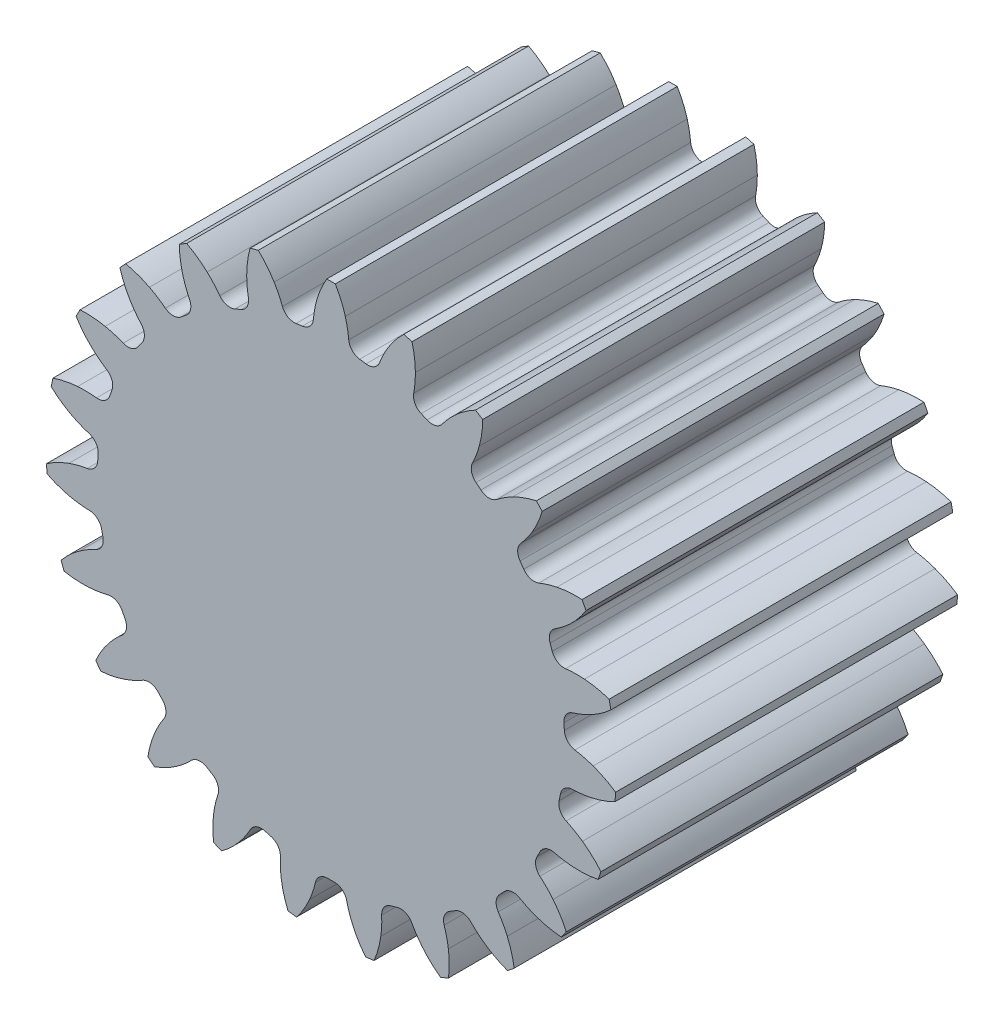
SolidWorks part; units mm, degrees
ref_plane "Front Plane" through (0, 0, 0) normal (0, 0, 1) x (1, 0, 0)
ref_plane "Top Plane" through (0, 0, 0) normal (0, 1, 0) x (1, 0, 0)
ref_plane "Right Plane" through (0, 0, 0) normal (1, 0, 0) x (0, 0, -1)
sketch "Sketch1" plane through (0, 0, 0) normal (0, 0, 1) x (1, 0, 0)
  line L0 (0, 50) -> (0, -50) construction
  circle A0 centre (0, 0) radius 46 construction
  circle A1 centre (0, 0) radius 50 construction
  arc A2 (-5.0261, 40.6908) -> (-6.1385, 40.5379) centre (0, 0) ccw
  arc A3 (-0.75, 49.9944) -> (0.75, 49.9944) centre (0, 0) cw
  arc A4 (0.75, 49.9944) -> (2.5, 45.932) centre (-13.7626, 41.3345) cw
  arc A5 (2.5, 45.932) -> (3.1051, 42.6729) centre (-14.8692, 41.0216) cw
  arc A6 (3.1051, 42.6729) -> (5.0261, 40.6908) centre (5.2958, 42.8742) ccw
  arc A7 (-3.1051, 42.6729) -> (-5.0261, 40.6908) centre (-5.2958, 42.8742) cw
  arc A8 (-2.5, 45.932) -> (-3.1051, 42.6729) centre (14.8692, 41.0216) ccw
  arc A9 (-0.75, 49.9944) -> (-2.5, 45.932) centre (13.7626, 41.3345) ccw
  arc A10 (8.5231, 41.9282) -> (6.1385, 40.5379) centre (6.4679, 42.7131) cw
  arc A11 (9.985, 44.9032) -> (8.5231, 41.9282) centre (25.3853, 35.4887) ccw
  arc A12 (12.7661, 48.3428) -> (9.985, 44.9032) centre (24.4042, 36.0886) ccw
  arc A13 (12.7661, 48.3428) -> (14.2105, 47.9381) centre (0, 0) cw
  arc A14 (14.2105, 47.9381) -> (14.7996, 43.5542) centre (-2.1004, 43.5148) cw
  arc A15 (14.7996, 43.5542) -> (14.5029, 40.2527) centre (-3.2503, 43.5121) cw
  arc A16 (14.5029, 40.2527) -> (15.818, 37.8258) centre (16.6668, 39.8555) ccw
  arc A17 (19.5191, 38.0739) -> (16.8478, 37.3785) centre (17.7519, 39.3842) cw
  arc A18 (21.7295, 40.5442) -> (19.5191, 38.0739) centre (34.0187, 27.3238) ccw
  arc A19 (25.3355, 43.1059) -> (21.7295, 40.5442) centre (33.2358, 28.1661) ccw
  arc A20 (25.3355, 43.1059) -> (26.6171, 42.3265) centre (0, 0) cw
  arc A21 (26.6171, 42.3265) -> (26.0016, 37.9462) centre (9.7177, 42.4678) cw
  arc A22 (26.0016, 37.9462) -> (24.8252, 34.8472) centre (8.6096, 42.7755) cw
  arc A23 (24.8252, 34.8472) -> (25.4367, 32.1555) centre (26.8016, 33.8809) ccw
  arc A24 (29.0675, 31.3958) -> (26.3077, 31.4469) centre (27.7193, 33.1343) cw
  arc A25 (31.8624, 33.1781) -> (29.0675, 31.3958) centre (40.1291, 17.1325) ccw
  arc A26 (36.0258, 34.6719) -> (31.8624, 33.1781) centre (39.6024, 18.1548) ccw
  arc A27 (36.0258, 34.6719) -> (37.0496, 33.5757) centre (0, 0) cw
  arc A28 (37.0496, 33.5757) -> (35.2752, 29.524) centre (20.815, 38.2712) cw
  arc A29 (35.2752, 29.524) -> (33.3063, 26.8572) centre (19.831, 38.8664) cw
  arc A30 (33.3063, 26.8572) -> (33.1689, 24.1003) centre (34.9487, 25.3935) ccw
  arc A31 (36.4601, 22.3893) -> (33.8164, 23.183) centre (35.6309, 24.427) cw
  arc A32 (39.6322, 23.3514) -> (36.4601, 22.3893) centre (43.2633, 5.6704) ccw
  arc A33 (44.0442, 23.6666) -> (39.6322, 23.3514) centre (43.0319, 6.7969) ccw
  arc A34 (44.0442, 23.6666) -> (44.7343, 22.3347) centre (0, 0) cw
  arc A35 (44.7343, 22.3347) -> (41.9325, 18.912) centre (30.3686, 31.2362) cw
  arc A36 (41.9325, 18.912) -> (39.3172, 16.8754) centre (29.5817, 32.0748) cw
  arc A37 (39.3172, 16.8754) -> (38.4411, 14.2578) centre (40.5038, 15.0228) ccw
  arc A38 (41.1486, 11.7222) -> (38.8171, 13.1998) centre (40.8999, 13.9081) cw
  arc A39 (44.4627, 11.7929) -> (41.1486, 11.7222) centre (43.1888, -6.2121) ccw
  arc A40 (48.7961, 10.906) -> (44.4627, 11.7929) centre (43.27, -5.065) ccw
  arc A41 (48.7961, 10.906) -> (49.1013, 9.4373) centre (0, 0) cw
  arc A42 (49.1013, 9.4373) -> (45.4799, 6.8974) centre (37.6698, 21.8845) cw
  arc A43 (45.4799, 6.8974) -> (42.4121, 5.6419) centre (37.1384, 22.9043) cw
  arc A44 (42.4121, 5.6419) -> (40.8623, 3.3578) centre (43.0549, 3.5379) ccw
  arc A45 (42.7853, 0.1857) -> (40.9389, 2.2376) centre (43.1356, 2.3577) cw
  arc A46 (45.9955, -0.6403) -> (42.7853, 0.1857) centre (39.9113, -17.634) ccw
  arc A47 (49.929, -2.6635) -> (45.9955, -0.6403) centre (40.2989, -16.5513) ccw
  arc A48 (49.929, -2.6635) -> (49.8266, -4.16) centre (0, 0) cw
  arc A49 (49.8266, -4.16) -> (45.6543, -5.6287) centre (42.1773, 10.9098) cw
  arc A50 (45.6543, -5.6287) -> (42.3615, -6.0099) centre (41.9407, 12.0352) cw
  arc A51 (42.3615, -6.0099) -> (40.2529, -7.7913) centre (42.4128, -8.2093) ccw
  arc A52 (41.2488, -11.3645) -> (40.0245, -8.8906) centre (42.1721, -9.3676) cw
  arc A53 (44.1171, -13.026) -> (41.2488, -11.3645) centre (33.6737, -27.748) ccw
  arc A54 (47.3589, -16.0354) -> (44.1171, -13.026) centre (34.339, -26.81) ccw
  arc A55 (47.3589, -16.0354) -> (46.8566, -17.4488) centre (0, 0) cw
  arc A56 (46.8566, -17.4488) -> (42.4427, -17.7373) centre (43.5567, -0.8741) cw
  arc A57 (42.4427, -17.7373) -> (39.1692, -17.2161) centre (43.6325, 0.2734) cw
  arc A58 (39.1692, -17.2161) -> (36.6582, -18.3624) centre (38.6252, -19.3478) ccw
  arc A59 (36.6531, -22.0719) -> (36.1416, -19.3593) centre (38.0809, -20.3981) cw
  arc A60 (38.9668, -24.4457) -> (36.6531, -22.0719) centre (24.9386, -35.8041) ccw
  arc A61 (41.2764, -28.218) -> (38.9668, -24.4457) centre (25.8324, -35.0804) ccw
  arc A62 (41.2764, -28.218) -> (40.4114, -29.4435) centre (0, 0) cw
  arc A63 (40.4114, -29.4435) -> (36.0834, -28.5305) centre (41.7056, -12.5931) cw
  arc A64 (36.0834, -28.5305) -> (33.0718, -27.1454) centre (42.0882, -11.5086) cw
  arc A65 (33.0718, -27.1454) -> (30.3446, -27.5718) centre (31.9729, -29.0512) ccw
  arc A66 (29.339, -31.1423) -> (29.5783, -28.3923) centre (31.1654, -29.9158) cw
  arc A67 (30.9264, -34.0523) -> (29.339, -31.1423) centre (14.354, -41.2047) ccw
  arc A68 (32.1326, -38.3079) -> (30.9264, -34.0523) centre (15.4099, -40.749) ccw
  arc A69 (32.1326, -38.3079) -> (30.9691, -39.2545) centre (0, 0) cw
  arc A70 (30.9691, -39.2545) -> (27.0479, -37.2077) centre (36.7615, -23.3782) cw
  arc A71 (27.0479, -37.2077) -> (24.5217, -35.0614) centre (37.4225, -22.4371) cw
  arc A72 (24.5217, -35.0614) -> (21.7806, -34.7362) centre (22.9493, -36.6001) ccw
  arc A73 (19.8489, -37.903) -> (20.8213, -35.3196) centre (21.9385, -37.2148) cw
  arc A74 (20.5924, -41.1334) -> (19.8489, -37.903) centre (2.7048, -43.5494) ccw
  arc A75 (20.6057, -45.5566) -> (20.5924, -41.1334) centre (3.8445, -43.3955) ccw
  arc A76 (20.6057, -45.5566) -> (19.2299, -46.1542) centre (0, 0) cw
  arc A77 (19.2299, -46.1542) -> (16.0063, -43.1254) centre (29.0909, -32.4294) cw
  arc A78 (16.0063, -43.1254) -> (14.1529, -40.3771) centre (29.9813, -31.7016) cw
  arc A79 (14.1529, -40.3771) -> (11.6012, -39.3244) centre (12.2237, -41.4345) ccw
  arc A80 (8.8868, -41.8526) -> (10.5201, -39.6274) centre (11.0846, -41.7537) cw
  arc A81 (8.7311, -45.1638) -> (8.8868, -41.8526) centre (-9.145, -42.6642) ccw
  arc A82 (7.5506, -49.4266) -> (8.7311, -45.1638) centre (-8.006, -42.8235) ccw
  arc A83 (7.5506, -49.4266) -> (6.0646, -49.6308) centre (0, 0) cw
  arc A84 (6.0646, -49.6308) -> (3.7777, -45.8446) centre (19.2628, -39.0755) cw
  arc A85 (3.7777, -45.8446) -> (2.7345, -42.6982) centre (20.3165, -38.6148) cw
  arc A86 (2.7345, -42.6982) -> (0.5614, -40.9962) centre (0.5915, -43.196) ccw
  arc A87 (-2.7345, -42.6982) -> (-0.5614, -40.9962) centre (-0.5915, -43.196) cw
  arc A88 (-3.7777, -45.8446) -> (-2.7345, -42.6982) centre (-20.3165, -38.6148) ccw
  arc A89 (-6.0646, -49.6308) -> (-3.7777, -45.8446) centre (-19.2628, -39.0755) ccw
  arc A90 (-6.0646, -49.6308) -> (-7.5506, -49.4266) centre (0, 0) cw
  arc A91 (-7.5506, -49.4266) -> (-8.7311, -45.1638) centre (8.006, -42.8235) cw
  arc A92 (-8.7311, -45.1638) -> (-8.8868, -41.8526) centre (9.145, -42.6642) cw
  arc A93 (-8.8868, -41.8526) -> (-10.5201, -39.6274) centre (-11.0846, -41.7537) ccw
  arc A94 (-14.1529, -40.3771) -> (-11.6012, -39.3244) centre (-12.2237, -41.4345) cw
  arc A95 (-16.0063, -43.1254) -> (-14.1529, -40.3771) centre (-29.9813, -31.7016) ccw
  arc A96 (-19.2299, -46.1542) -> (-16.0063, -43.1254) centre (-29.0909, -32.4294) ccw
  arc A97 (-19.2299, -46.1542) -> (-20.6057, -45.5566) centre (0, 0) cw
  arc A98 (-20.6057, -45.5566) -> (-20.5924, -41.1334) centre (-3.8445, -43.3955) cw
  arc A99 (-20.5924, -41.1334) -> (-19.8489, -37.903) centre (-2.7048, -43.5494) cw
  arc A100 (-19.8489, -37.903) -> (-20.8213, -35.3196) centre (-21.9385, -37.2148) ccw
  arc A101 (-24.5217, -35.0614) -> (-21.7806, -34.7362) centre (-22.9493, -36.6001) cw
  arc A102 (-27.0479, -37.2077) -> (-24.5217, -35.0614) centre (-37.4225, -22.4371) ccw
  arc A103 (-30.9691, -39.2545) -> (-27.0479, -37.2077) centre (-36.7615, -23.3782) ccw
  arc A104 (-30.9691, -39.2545) -> (-32.1326, -38.3079) centre (0, 0) cw
  arc A105 (-32.1326, -38.3079) -> (-30.9264, -34.0523) centre (-15.4099, -40.749) cw
  arc A106 (-30.9264, -34.0523) -> (-29.339, -31.1423) centre (-14.354, -41.2047) cw
  arc A107 (-29.339, -31.1423) -> (-29.5783, -28.3923) centre (-31.1654, -29.9158) ccw
  arc A108 (-33.0718, -27.1454) -> (-30.3446, -27.5718) centre (-31.9729, -29.0512) cw
  arc A109 (-36.0834, -28.5305) -> (-33.0718, -27.1454) centre (-42.0882, -11.5086) ccw
  arc A110 (-40.4114, -29.4435) -> (-36.0834, -28.5305) centre (-41.7056, -12.5931) ccw
  arc A111 (-40.4114, -29.4435) -> (-41.2764, -28.218) centre (0, 0) cw
  arc A112 (-41.2764, -28.218) -> (-38.9668, -24.4457) centre (-25.8324, -35.0804) cw
  arc A113 (-38.9668, -24.4457) -> (-36.6531, -22.0719) centre (-24.9386, -35.8041) cw
  arc A114 (-36.6531, -22.0719) -> (-36.1416, -19.3593) centre (-38.0809, -20.3981) ccw
  arc A115 (-39.1692, -17.2161) -> (-36.6582, -18.3624) centre (-38.6252, -19.3478) cw
  arc A116 (-42.4427, -17.7373) -> (-39.1692, -17.2161) centre (-43.6325, 0.2734) ccw
  arc A117 (-46.8566, -17.4488) -> (-42.4427, -17.7373) centre (-43.5567, -0.8741) ccw
  arc A118 (-46.8566, -17.4488) -> (-47.3589, -16.0354) centre (0, 0) cw
  arc A119 (-47.3589, -16.0354) -> (-44.1171, -13.026) centre (-34.339, -26.81) cw
  arc A120 (-44.1171, -13.026) -> (-41.2488, -11.3645) centre (-33.6737, -27.748) cw
  arc A121 (-41.2488, -11.3645) -> (-40.0245, -8.8906) centre (-42.1721, -9.3676) ccw
  arc A122 (-42.3615, -6.0099) -> (-40.2529, -7.7913) centre (-42.4128, -8.2093) cw
  arc A123 (-45.6543, -5.6287) -> (-42.3615, -6.0099) centre (-41.9407, 12.0352) ccw
  arc A124 (-49.8266, -4.16) -> (-45.6543, -5.6287) centre (-42.1773, 10.9098) ccw
  arc A125 (-49.8266, -4.16) -> (-49.929, -2.6635) centre (0, 0) cw
  arc A126 (-49.929, -2.6635) -> (-45.9955, -0.6403) centre (-40.2989, -16.5513) cw
  arc A127 (-45.9955, -0.6403) -> (-42.7853, 0.1857) centre (-39.9113, -17.634) cw
  arc A128 (-42.7853, 0.1857) -> (-40.9389, 2.2376) centre (-43.1356, 2.3577) ccw
  arc A129 (-42.4121, 5.6419) -> (-40.8623, 3.3578) centre (-43.0549, 3.5379) cw
  arc A130 (-45.4799, 6.8974) -> (-42.4121, 5.6419) centre (-37.1384, 22.9043) ccw
  arc A131 (-49.1013, 9.4373) -> (-45.4799, 6.8974) centre (-37.6698, 21.8845) ccw
  arc A132 (-49.1013, 9.4373) -> (-48.7961, 10.906) centre (0, 0) cw
  arc A133 (-48.7961, 10.906) -> (-44.4627, 11.7929) centre (-43.27, -5.065) cw
  arc A134 (-44.4627, 11.7929) -> (-41.1486, 11.7222) centre (-43.1888, -6.2121) cw
  arc A135 (-41.1486, 11.7222) -> (-38.8171, 13.1998) centre (-40.8999, 13.9081) ccw
  arc A136 (-39.3172, 16.8754) -> (-38.4411, 14.2578) centre (-40.5038, 15.0228) cw
  arc A137 (-41.9325, 18.912) -> (-39.3172, 16.8754) centre (-29.5817, 32.0748) ccw
  arc A138 (-44.7343, 22.3347) -> (-41.9325, 18.912) centre (-30.3686, 31.2362) ccw
  arc A139 (-44.7343, 22.3347) -> (-44.0442, 23.6666) centre (0, 0) cw
  arc A140 (-44.0442, 23.6666) -> (-39.6322, 23.3514) centre (-43.0319, 6.7969) cw
  arc A141 (-39.6322, 23.3514) -> (-36.4601, 22.3893) centre (-43.2633, 5.6704) cw
  arc A142 (-36.4601, 22.3893) -> (-33.8164, 23.183) centre (-35.6309, 24.427) ccw
  arc A143 (-33.3063, 26.8572) -> (-33.1689, 24.1003) centre (-34.9487, 25.3935) cw
  arc A144 (-35.2752, 29.524) -> (-33.3063, 26.8572) centre (-19.831, 38.8664) ccw
  arc A145 (-37.0496, 33.5757) -> (-35.2752, 29.524) centre (-20.815, 38.2712) ccw
  arc A146 (-37.0496, 33.5757) -> (-36.0258, 34.6719) centre (0, 0) cw
  arc A147 (-36.0258, 34.6719) -> (-31.8624, 33.1781) centre (-39.6024, 18.1548) cw
  arc A148 (-31.8624, 33.1781) -> (-29.0675, 31.3958) centre (-40.1291, 17.1325) cw
  arc A149 (-29.0675, 31.3958) -> (-26.3077, 31.4469) centre (-27.7193, 33.1343) ccw
  arc A150 (-24.8252, 34.8472) -> (-25.4367, 32.1555) centre (-26.8016, 33.8809) cw
  arc A151 (-26.0016, 37.9462) -> (-24.8252, 34.8472) centre (-8.6096, 42.7755) ccw
  arc A152 (-26.6171, 42.3265) -> (-26.0016, 37.9462) centre (-9.7177, 42.4678) ccw
  arc A153 (-26.6171, 42.3265) -> (-25.3355, 43.1059) centre (0, 0) cw
  arc A154 (-25.3355, 43.1059) -> (-21.7295, 40.5442) centre (-33.2358, 28.1661) cw
  arc A155 (-21.7295, 40.5442) -> (-19.5191, 38.0739) centre (-34.0187, 27.3238) cw
  arc A156 (-19.5191, 38.0739) -> (-16.8478, 37.3785) centre (-17.7519, 39.3842) ccw
  arc A157 (-14.5029, 40.2527) -> (-15.818, 37.8258) centre (-16.6668, 39.8555) cw
  arc A158 (-14.7996, 43.5542) -> (-14.5029, 40.2527) centre (3.2503, 43.5121) ccw
  arc A159 (-14.2105, 47.9381) -> (-14.7996, 43.5542) centre (2.1004, 43.5148) ccw
  arc A160 (-14.2105, 47.9381) -> (-12.7661, 48.3428) centre (0, 0) cw
  arc A161 (-12.7661, 48.3428) -> (-9.985, 44.9032) centre (-24.4042, 36.0886) cw
  arc A162 (-9.985, 44.9032) -> (-8.5231, 41.9282) centre (-25.3853, 35.4887) cw
  arc A163 (-8.5231, 41.9282) -> (-6.1385, 40.5379) centre (-6.4679, 42.7131) ccw
  arc A164 (6.1385, 40.5379) -> (5.0261, 40.6908) centre (0, 0) ccw
  arc A165 (16.8478, 37.3785) -> (15.818, 37.8258) centre (0, 0) ccw
  arc A166 (26.3077, 31.4469) -> (25.4367, 32.1555) centre (0, 0) ccw
  arc A167 (33.8164, 23.183) -> (33.1689, 24.1003) centre (0, 0) ccw
  arc A168 (38.8171, 13.1998) -> (38.4411, 14.2578) centre (0, 0) ccw
  arc A169 (40.9389, 2.2376) -> (40.8623, 3.3578) centre (0, 0) ccw
  arc A170 (40.0245, -8.8906) -> (40.2529, -7.7913) centre (0, 0) ccw
  arc A171 (36.1416, -19.3593) -> (36.6582, -18.3624) centre (0, 0) ccw
  arc A172 (29.5783, -28.3923) -> (30.3446, -27.5718) centre (0, 0) ccw
  arc A173 (20.8213, -35.3196) -> (21.7806, -34.7362) centre (0, 0) ccw
  arc A174 (10.5201, -39.6274) -> (11.6012, -39.3244) centre (0, 0) ccw
  arc A175 (-0.5614, -40.9962) -> (0.5614, -40.9962) centre (0, 0) ccw
  arc A176 (-11.6012, -39.3244) -> (-10.5201, -39.6274) centre (0, 0) ccw
  arc A177 (-21.7806, -34.7362) -> (-20.8213, -35.3196) centre (0, 0) ccw
  arc A178 (-30.3446, -27.5718) -> (-29.5783, -28.3923) centre (0, 0) ccw
  arc A179 (-36.6582, -18.3624) -> (-36.1416, -19.3593) centre (0, 0) ccw
  arc A180 (-40.2529, -7.7913) -> (-40.0245, -8.8906) centre (0, 0) ccw
  arc A181 (-40.8623, 3.3578) -> (-40.9389, 2.2376) centre (0, 0) ccw
  arc A182 (-38.4411, 14.2578) -> (-38.8171, 13.1998) centre (0, 0) ccw
  arc A183 (-33.1689, 24.1003) -> (-33.8164, 23.183) centre (0, 0) ccw
  arc A184 (-25.4367, 32.1555) -> (-26.3077, 31.4469) centre (0, 0) ccw
  arc A185 (-15.818, 37.8258) -> (-16.8478, 37.3785) centre (0, 0) ccw
  point P332 (0, 0)
  dimension "D1" = 92
  dimension "D2" = 100
  dimension "D3" = 82
  dimension "D7" = 16.9
  dimension "D8" = 2.2
  dimension "D6" = 18.05
  dimension "D4" = 0.75
  dimension "D5" = 2.5
extrude "Boss-Extrude1" add sketch "Sketch1" along normal blind 60
